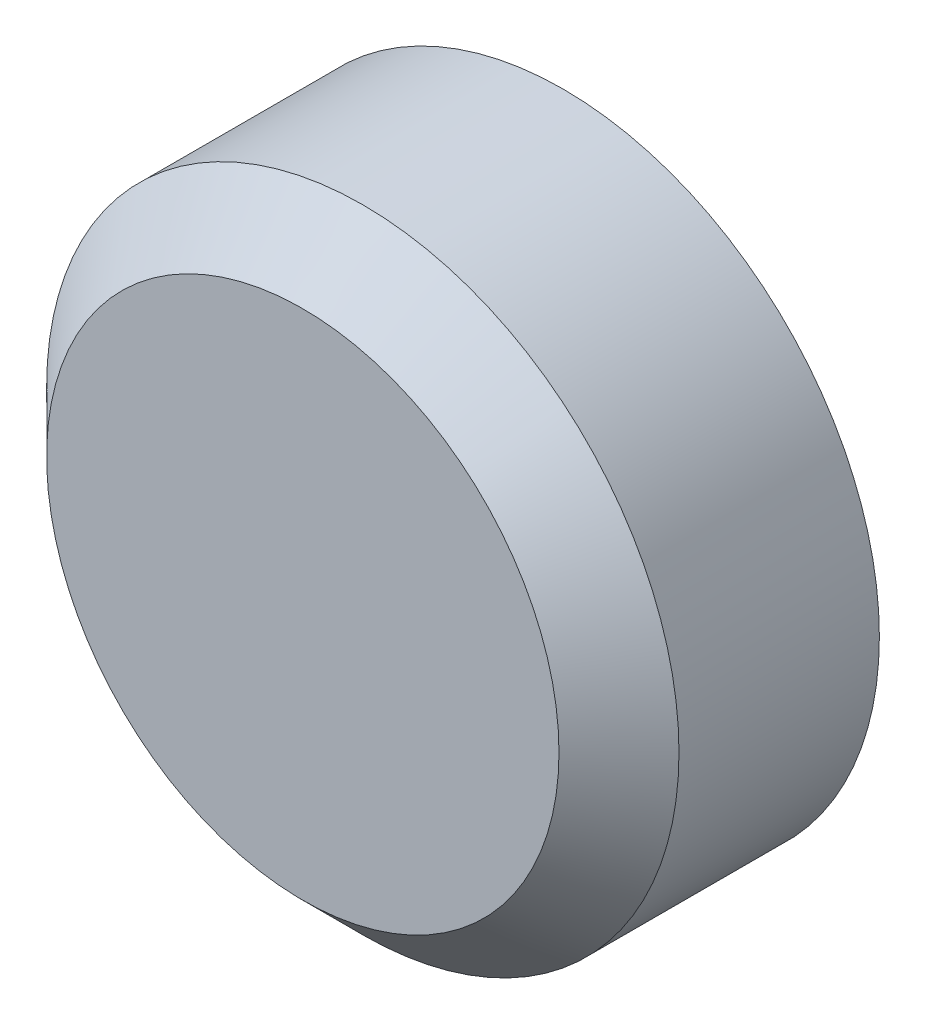
SolidWorks part; units mm, degrees
material "Béryllium"
ref_plane "Plan de face" through (0, 0, 0) normal (0, 0, 1) x (1, 0, 0)
ref_plane "Plan de dessus" through (0, 0, 0) normal (0, 1, 0) x (1, 0, 0)
ref_plane "Plan de droite" through (0, 0, 0) normal (1, 0, 0) x (0, 0, -1)
sketch "Esquisse1" plane through (0, 0, 0) normal (0, 0, 1) x (1, 0, 0)
  circle A0 centre (0, 0) radius 2.635
  dimension "D1" = 5.27
extrude "Boss.-Extru.1" add sketch "Esquisse1" along normal up to surface (2.17 mm away) contours A0
chamfer "Chanfrein1" distance 0.5 1 edges at (2.635, 0, 2.17)
